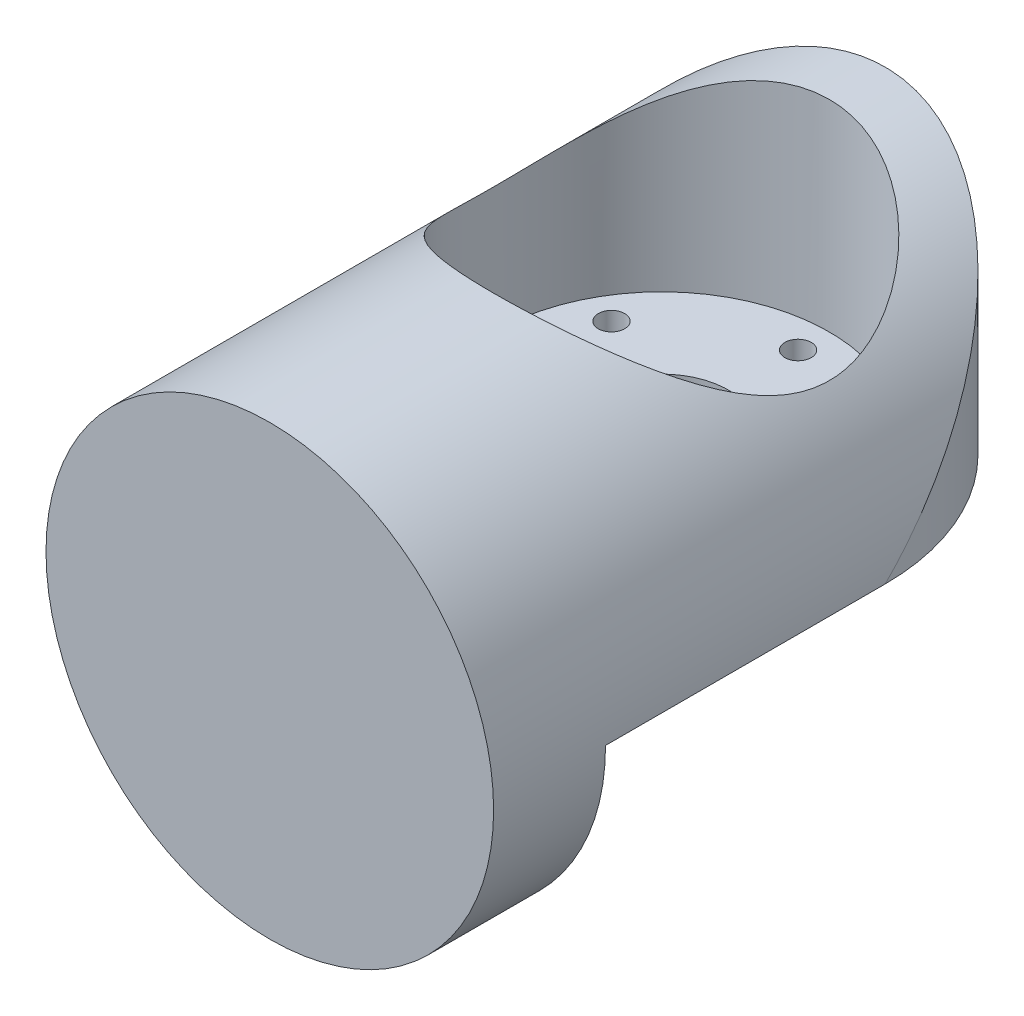
SolidWorks part; units mm, degrees
ref_plane "Front Plane" through (0, 0, 0) normal (0, 0, 1) x (1, 0, 0)
ref_plane "Top Plane" through (0, 0, 0) normal (0, 1, 0) x (1, 0, 0)
ref_plane "Right Plane" through (0, 0, 0) normal (1, 0, 0) x (0, 0, -1)
sketch "Sketch1" plane through (0, 0, 0) normal (0, 0, 1) x (1, 0, 0)
  circle A0 centre (0, 0) radius 25.4
  dimension "D1" = 50.8
extrude "Boss-Extrude1" add sketch "Sketch1" along normal blind 12.7
sketch "Sketch2" plane through (0, 0, 0) normal (0, 1, 0) x (1, 0, 0)
  line L0 (25.4, -12.7) -> (25.4, 0) construction
  line L1 (-25.4, 0) -> (25.4, 0)
  line L2 (-25.4, 0) -> (-25.4, 31.75)
  line L3 (-25.4, 31.75) -> (25.4, 31.75)
  line L4 (25.4, 0) -> (25.4, 31.75)
  circle A0 centre (0, 31.75) radius 25.4
  dimension "D1" = 31.75
extrude "Boss-Extrude2" add sketch "Sketch2" along normal blind 25.4 contours A0 | L2 L1 L4 L3
sketch "Sketch4" plane through (0, 25.4, 0) normal (0, -1, 0) x (1, 0, 0)
  circle A0 centre (0, -31.75) radius 19.05
  arc A1 (-25.4, -31.75) -> (25.4, -31.75) centre (0, -31.75) ccw construction
  dimension "D1" = 38.1
extrude "Cut-Extrude2" cut sketch "Sketch4" along normal offset from surface (22.86 mm away) 2.54 up to face at (0, 0, -22.225)
sketch "Sketch3" plane through (0, 0, 0) normal (0, 0, 1) x (1, 0, 0)
  line L0 (25.4, 0) -> (25.4, 25.4) construction
  line L1 (25.4, 25.4) -> (0, 25.4) construction
  line L2 (0, 25.4) -> (-25.4, 25.4) construction
  line L3 (-25.4, 25.4) -> (-25.4, 0) construction
  line L4 (25.4, 0) -> (25.4, 25.4)
  line L5 (25.4, 25.4) -> (0, 25.4)
  line L6 (0, 25.4) -> (-25.4, 25.4)
  line L7 (-25.4, 25.4) -> (-25.4, 0)
  arc A0 (25.4, 0) -> (0, 25.4) centre (0, 0) ccw construction
  arc A1 (0, 25.4) -> (-25.4, 0) centre (0, 0) ccw construction
  arc A2 (25.4, 0) -> (0, 25.4) centre (0, 0) ccw
  arc A3 (0, 25.4) -> (-25.4, 0) centre (0, 0) ccw
extrude "Cut-Extrude1" cut sketch "Sketch3" against normal through all contours L5 L4 A2 | A3 L7 L6
sketch "Sketch5" plane through (0, 2.54, 0) normal (0, 1, 0) x (1, 0, 0)
  circle A0 centre (0, 31.75) radius 7.62
  circle A1 centre (0, 31.75) radius 19.05 construction
  circle A2 centre (0, 31.75) radius 15.5 construction
  circle A3 centre (0, 47.25) radius 1.5
  circle A4 centre (13.4234, 39.5) radius 1.5
  circle A5 centre (13.4234, 24) radius 1.5
  circle A6 centre (0, 16.25) radius 1.5
  circle A7 centre (-13.4234, 24) radius 1.5
  circle A8 centre (-13.4234, 39.5) radius 1.5
  point P8 (0, 19.5768)
  dimension "D1" = 15.24
  dimension "D3" = 31
  dimension "D4" = 3
  dimension "D2" = 6
extrude "Cut-Extrude3" cut sketch "Sketch5" against normal through all
